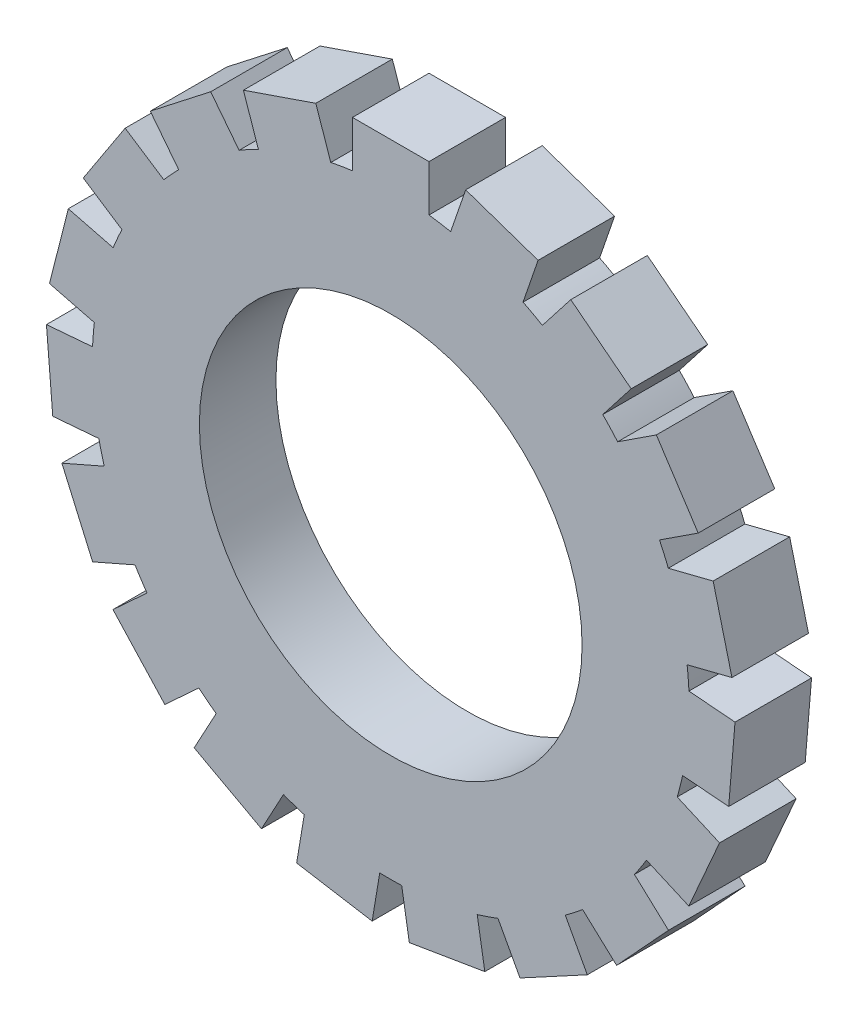
SolidWorks part; units mm, degrees
material "AISI 4340 Steel, annealed"
ref_plane "Front Plane" through (0, 0, 0) normal (0, 0, 1) x (1, 0, 0)
ref_plane "Top Plane" through (0, 0, 0) normal (0, 1, 0) x (1, 0, 0)
ref_plane "Right Plane" through (0, 0, 0) normal (1, 0, 0) x (0, 0, -1)
sketch "Sketch1" plane through (0, 0, 0) normal (0, 0, 1) x (1, 0, 0)
  line L1 (-5, 44.7214) -> (-5, 38.6782)
  line L2 (-5, 44.7214) -> (5, 44.7214)
  line L3 (5, 44.7214) -> (5, 38.6782)
  line L4 (9.7919, 43.9217) -> (7.8297, 38.206)
  line L5 (9.7919, 43.9217) -> (19.2501, 40.6747)
  line L6 (19.2501, 40.6747) -> (17.2879, 34.959)
  line L8 (23.5227, 38.3625) -> (19.8109, 33.5936)
  line L9 (23.5227, 38.3625) -> (31.4141, 32.2204)
  line L10 (31.4141, 32.2204) -> (27.7023, 27.4514)
  line L12 (34.7045, 28.6461) -> (29.6453, 25.3408)
  line L13 (34.7045, 28.6461) -> (40.174, 20.2744)
  line L14 (40.174, 20.2744) -> (35.1148, 16.9691)
  line L16 (42.1255, 15.8254) -> (36.2672, 14.3419)
  line L17 (42.1255, 15.8254) -> (44.5803, 6.1314)
  line L18 (44.5803, 6.1314) -> (38.722, 4.6479)
  line L20 (44.9815, 1.2899) -> (38.959, 1.7889)
  line L21 (44.9815, 1.2899) -> (44.1557, -8.676)
  line L22 (44.1557, -8.676) -> (38.1332, -8.1769)
  line L24 (42.9631, -13.3855) -> (37.4289, -10.958)
  line L25 (42.9631, -13.3855) -> (38.9462, -22.5432)
  line L26 (38.9462, -22.5432) -> (33.4119, -20.1157)
  line L28 (36.289, -26.6103) -> (31.8429, -22.5174)
  line L29 (36.289, -26.6103) -> (29.5162, -33.9676)
  line L30 (29.5162, -33.9676) -> (25.07, -29.8746)
  line L32 (25.6824, -36.9515) -> (22.8061, -31.6367)
  line L33 (25.6824, -36.9515) -> (16.8876, -41.711)
  line L34 (16.8876, -41.711) -> (14.0114, -36.3962)
  line L36 (12.2927, -43.2884) -> (11.298, -37.3277)
  line L37 (12.2927, -43.2884) -> (2.4291, -44.9344)
  line L38 (2.4291, -44.9344) -> (1.4344, -38.9736)
  line L40 (-2.4291, -44.9344) -> (-1.4344, -38.9736)
  line L41 (-2.4291, -44.9344) -> (-12.2927, -43.2884)
  line L42 (-12.2927, -43.2884) -> (-11.298, -37.3277)
  line L44 (-16.8876, -41.711) -> (-14.0114, -36.3962)
  line L45 (-16.8876, -41.711) -> (-25.6824, -36.9515)
  line L46 (-25.6824, -36.9515) -> (-22.8061, -31.6367)
  line L48 (-29.5162, -33.9676) -> (-25.07, -29.8746)
  line L49 (-29.5162, -33.9676) -> (-36.289, -26.6103)
  line L50 (-36.289, -26.6103) -> (-31.8429, -22.5174)
  line L52 (-38.9462, -22.5432) -> (-33.4119, -20.1157)
  line L53 (-38.9462, -22.5432) -> (-42.9631, -13.3855)
  line L54 (-42.9631, -13.3855) -> (-37.4289, -10.958)
  line L56 (-44.1557, -8.676) -> (-38.1332, -8.1769)
  line L57 (-44.1557, -8.676) -> (-44.9815, 1.2899)
  line L58 (-44.9815, 1.2899) -> (-38.959, 1.7889)
  line L60 (-44.5803, 6.1314) -> (-38.722, 4.6479)
  line L61 (-44.5803, 6.1314) -> (-42.1255, 15.8254)
  line L62 (-42.1255, 15.8254) -> (-36.2672, 14.3419)
  line L64 (-40.174, 20.2744) -> (-35.1148, 16.9691)
  line L65 (-40.174, 20.2744) -> (-34.7045, 28.6461)
  line L66 (-34.7045, 28.6461) -> (-29.6453, 25.3408)
  line L68 (-31.4141, 32.2204) -> (-27.7023, 27.4514)
  line L69 (-31.4141, 32.2204) -> (-23.5227, 38.3625)
  line L70 (-23.5227, 38.3625) -> (-19.8109, 33.5936)
  line L72 (-19.2501, 40.6747) -> (-17.2879, 34.959)
  line L73 (-19.2501, 40.6747) -> (-9.7919, 43.9217)
  line L74 (-9.7919, 43.9217) -> (-7.8297, 38.206)
  circle A0 centre (0, 0) radius 25
  circle A1 centre (0, 0) radius 39
  point P10 (0, 44.7214)
  point P18 (14.521, 42.2982)
  point P24 (27.4684, 35.2914)
  point P30 (37.4392, 24.4603)
  point P36 (43.3529, 10.9784)
  point P42 (44.5686, -3.6931)
  point P48 (40.9546, -17.9644)
  point P54 (32.9026, -30.289)
  point P60 (21.285, -39.3313)
  point P66 (7.3609, -44.1114)
  point P72 (-7.3609, -44.1114)
  point P78 (-21.285, -39.3313)
  point P84 (-32.9026, -30.289)
  point P90 (-40.9546, -17.9644)
  point P96 (-44.5686, -3.6931)
  point P102 (-43.3529, 10.9784)
  point P108 (-37.4392, 24.4603)
  point P114 (-27.4684, 35.2914)
  point P120 (-14.521, 42.2982)
  point P121 (0, 0)
  dimension "D2" = 50
  dimension "D3" = 19
extrude "Boss-Extrude1" add sketch "Sketch1" along normal blind 10 contours A1 A0 | A1 L62 L61 L60 | A1 L66 L65 L64 | A1 L70 L69 L68 | A1 L74 L73 L72 | A1 L6 L5 L4 | A1 L3 L2 L1 | A1 L10 L9 L8 | A1 L14 L13 L12 | A1 L18 L17 L16 | A1 L22 L21 L20 | A1 L26 L25 L24 | A1 L30 L29 L28 | A1 L58 L57 L56 | A1 L54 L53 L52 | A1 L50 L49 L48 | A1 L46 L45 L44 | A1 L42 L41 L40 | A1 L38 L37 L36 | A1 L34 L33 L32
